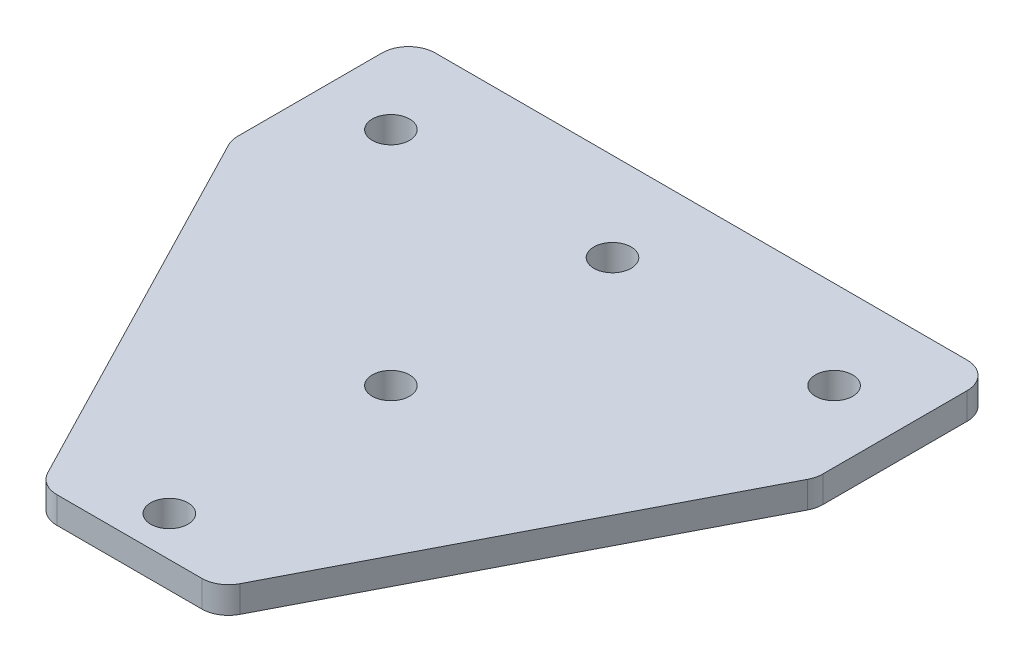
SolidWorks part; units mm, degrees
material "A-玻璃纤维"
ref_plane "前视基准面" through (0, 0, 0) normal (0, 0, 1) x (1, 0, 0)
ref_plane "上视基准面" through (0, 0, 0) normal (0, 1, 0) x (1, 0, 0)
ref_plane "右视基准面" through (0, 0, 0) normal (1, 0, 0) x (0, 0, -1)
sketch "草图1" plane through (0, 0, 0) normal (0, 1, 0) x (1, 0, 0)
  line L0 (-43.2884, 0) -> (46.6978, 0) construction
  line L1 (0, 0) -> (0, -44.5) construction
  line L2 (33, 10) -> (-33, 10)
  line L3 (-33, 10) -> (-33, -10)
  line L4 (-33, -10) -> (-10, -10)
  line L5 (-10, -10) -> (-10, -54.5)
  line L6 (-10, -54.5) -> (10, -54.5)
  line L7 (10, -54.5) -> (10, -10)
  line L8 (10, -10) -> (33, -10)
  line L9 (33, -10) -> (33, 10)
  line L10 (-33, -10) -> (-10, -54.5)
  line L11 (33, -10) -> (10, -54.5)
  circle A0 centre (0, 0) radius 2.1
  circle A1 centre (25, 0) radius 2.1
  circle A2 centre (-25, 0) radius 2.1
  circle A3 centre (0, -25) radius 2.1
  circle A4 centre (0, -50) radius 2.1
  dimension "D1" = 4.2
  dimension "D2" = 25
  dimension "D3" = 25
  dimension "D4" = 25
  dimension "D5" = 25
  dimension "D7" = 8
  dimension "D6" = 20
  dimension "D8" = 8
  dimension "D9" = 20
  dimension "D10" = 4.5
extrude "凸台-拉伸1" add sketch "草图1" along normal blind 3
fillet "圆角1" radius 3 6 edges at (33, 1.5, -10) (-33, 1.5, -10) (10, 1.5, 54.5) (-10, 1.5, 54.5) (-33, 1.5, 10) (33, 1.5, 10)
